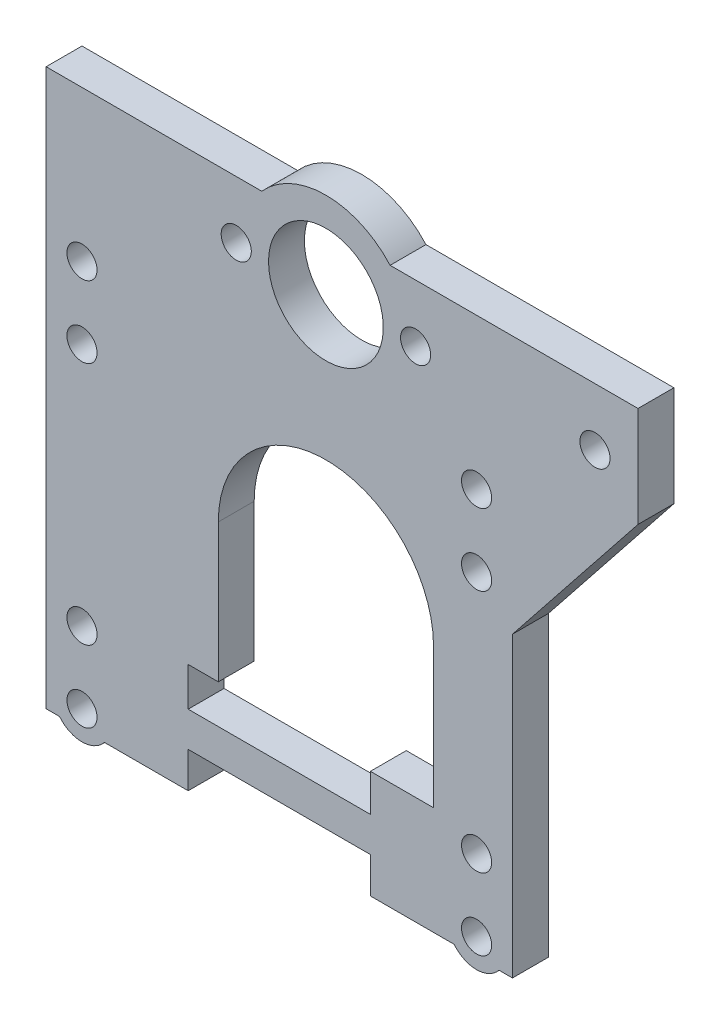
SolidWorks part; units mm, degrees
ref_plane "Front Plane" through (0, 0, 0) normal (0, 0, 1) x (1, 0, 0)
ref_plane "Top Plane" through (0, 0, 0) normal (0, 1, 0) x (1, 0, 0)
ref_plane "Right Plane" through (0, 0, 0) normal (1, 0, 0) x (0, 0, -1)
sketch "Sketch1" plane through (0, 0, 0) normal (0, 0, 1) x (1, 0, 0)
  line L1 (-65, 61.5) -> (0, 61.5)
  line L2 (-65, 61.5) -> (-65, 0)
  line L3 (-65, 0) -> (-63.1225, 0)
  line L4 (0, 61.5) -> (0, 0)
  line L5 (-56.8775, 0) -> (-45, 0)
  line L6 (-1.8775, 0) -> (0, 0)
  line L7 (-20, 0) -> (-8.1225, 0)
  line L9 (-45, 0) -> (-45, 5)
  line L10 (-45, 5) -> (-20, 5)
  line L11 (-20, 0) -> (-20, 5)
  line L13 (-45, 15.05) -> (-20, 15.05)
  line L14 (-45, 15.05) -> (-45, 9.95)
  line L15 (-45, 9.95) -> (-20, 9.95)
  line L16 (-20, 15.05) -> (-20, 9.95)
  circle A0 centre (-60, 56.5) radius 2.1
  circle A1 centre (-5, 56.5) radius 2.1
  circle A2 centre (-60, 46.5) radius 2.1
  circle A3 centre (-5, 46.5) radius 2.1
  circle A4 centre (-5, 12.5) radius 2.1
  circle A5 centre (-5, 2.5) radius 2.1
  circle A6 centre (-60, 2.5) radius 2.1
  circle A7 centre (-60, 12.5) radius 2.1
  arc A8 (-63.1225, 0) -> (-56.8775, 0) centre (-60, 2.5) ccw
  arc A9 (-8.1225, 0) -> (-1.8775, 0) centre (-5, 2.5) ccw
  point P35 (-45, 12.5)
  dimension "D1" = 4.2
  dimension "D2" = 4.2
  dimension "D3" = 4.2
  dimension "D4" = 4.2
  dimension "D5" = 5
  dimension "D6" = 5
  dimension "D7" = 10
  dimension "D8" = 10
  dimension "D9" = 5
  dimension "D11" = 55
  dimension "D14" = 8
  dimension "D15" = 8
  dimension "D10" = 5
  dimension "D12" = 61.5
  dimension "D16" = 5
  dimension "D17" = 20
  dimension "D18" = 20
  dimension "D19" = 25
  dimension "D20" = 15
  dimension "D21" = 5.1
extrude "Boss-Extrude1" add sketch "Sketch1" along normal blind 5
sketch "Sketch3" plane through (0, 0, 0) normal (0, 0, -1) x (-1, 0, 0)
  line L0 (41, 15.05) -> (41, 34.55)
  line L1 (20, 15.05) -> (45, 15.05) construction
  line L2 (11, 34.55) -> (11, 15.05)
  line L3 (41, 15.05) -> (11, 15.05)
  arc A0 (41, 34.55) -> (11, 34.55) centre (26, 34.55) ccw
  circle A1 centre (26, 34.55) radius 3.6 construction
  dimension "D1" = 30
extrude "Cut-Extrude2" cut sketch "Sketch3" against normal blind 5
sketch "Sketch4" plane through (0, 0, 0) normal (0, 0, -1) x (-1, 0, 0)
  line L0 (0, 41.5) -> (-17.5, 63.5)
  line L1 (-17.5, 63.5) -> (0, 41.5) construction
  line L2 (-17.5, 63.5) -> (-17.5, 77.5)
  line L5 (65, 61.5) -> (65, 77.5)
  line L10 (65, 77.5) -> (-17.5, 77.5)
  line L18 (65, 0) -> (65, 61.5)
  line L19 (65, 61.5) -> (0, 61.5)
  line L20 (0, 61.5) -> (0, 0)
  line L21 (0, 0) -> (1.8775, 0)
  line L22 (8.1225, 0) -> (20, 0)
  line L23 (20, 0) -> (20, 5)
  line L24 (20, 5) -> (45, 5)
  line L25 (45, 5) -> (45, 0)
  line L26 (45, 0) -> (56.8775, 0)
  line L27 (63.1225, 0) -> (65, 0)
  line L29 (65, 61.5) -> (0, 61.5)
  line L30 (0, 61.5) -> (0, 41.5)
  arc A0 (28.3171, 66.2394) -> (22.3115, 67.9523) centre (26, 69.5) ccw construction
  circle A1 centre (13.5, 69.5) radius 2.1 construction
  circle A2 centre (-11.5, 69.5) radius 2.1 construction
  circle A6 centre (38.5, 69.5) radius 2.1 construction
  circle A8 centre (-11.5, 69.5) radius 2.1
  arc A11 (1.8775, 0) -> (8.1225, 0) centre (5, 2.5) ccw
  arc A12 (56.8775, 0) -> (63.1225, 0) centre (60, 2.5) ccw
  circle A16 centre (13.5, 69.5) radius 2.1
  circle A17 centre (26, 69.5) radius 4
  circle A18 centre (38.5, 69.5) radius 2.1
  point P34 (13.5, 69.5)
  point P36 (-11.5, 69.5)
  point P37 (26, 69.5)
  point P39 (38.5, 69.5)
  dimension "D2" = 8
  dimension "D3" = 4.2
  dimension "D4" = 4.2
  dimension "D5" = 4.2
  dimension "D6" = 6
  dimension "D7" = 8
  dimension "D9" = 43.5
  dimension "D10" = 56
  dimension "D1" = 0
  dimension "D8" = 31
  dimension "D11" = 8
extrude "Boss-Extrude2" add sketch "Sketch4" against normal blind 5
sketch "Sketch5" plane through (0, 0, 0) normal (0, 0, -1) x (-1, 0, 0)
  line L0 (56.8775, 0) -> (45, 0) construction
  line L1 (19.8, 5) -> (45.2, 5)
  line L2 (19.8, 5) -> (19.8, 0)
  line L3 (19.8, 0) -> (45.2, 0)
  line L4 (45.2, 5) -> (45.2, 0)
  line L5 (20, 5) -> (20, 0) construction
  line L7 (11, 15.05) -> (20, 15.05) construction
  line L8 (45.2, 15.25) -> (19.8, 15.25)
  line L9 (45.2, 15.25) -> (45.2, 9.85)
  line L10 (45.2, 9.85) -> (19.8, 9.85)
  line L11 (19.8, 15.25) -> (19.8, 9.85)
  dimension "D1" = 25.4
  dimension "D2" = 0.2
  dimension "D3" = 5
  dimension "D4" = 5.4
  dimension "D5" = 0.2
  dimension "D6" = 25.4
extrude "Cut-Extrude3" cut sketch "Sketch5" against normal blind 10
sketch "Sketch6" plane through (0, 0, 0) normal (0, 0, -1) x (-1, 0, 0)
  line L0 (17.0557, 77.5) -> (34.9443, 77.5)
  line L1 (65, 77.5) -> (-17.5, 77.5) construction
  arc A0 (34.9443, 77.5) -> (17.0557, 77.5) centre (26, 69.5) ccw
  dimension "D1" = 24
extrude "Boss-Extrude3" add sketch "Sketch6" against normal blind 5
sketch "Sketch7" plane through (0, 0, 0) normal (0, 0, -1) x (-1, 0, 0)
  circle A0 centre (26, 69.5) radius 8
extrude "Cut-Extrude6" cut sketch "Sketch7" against normal blind 5
